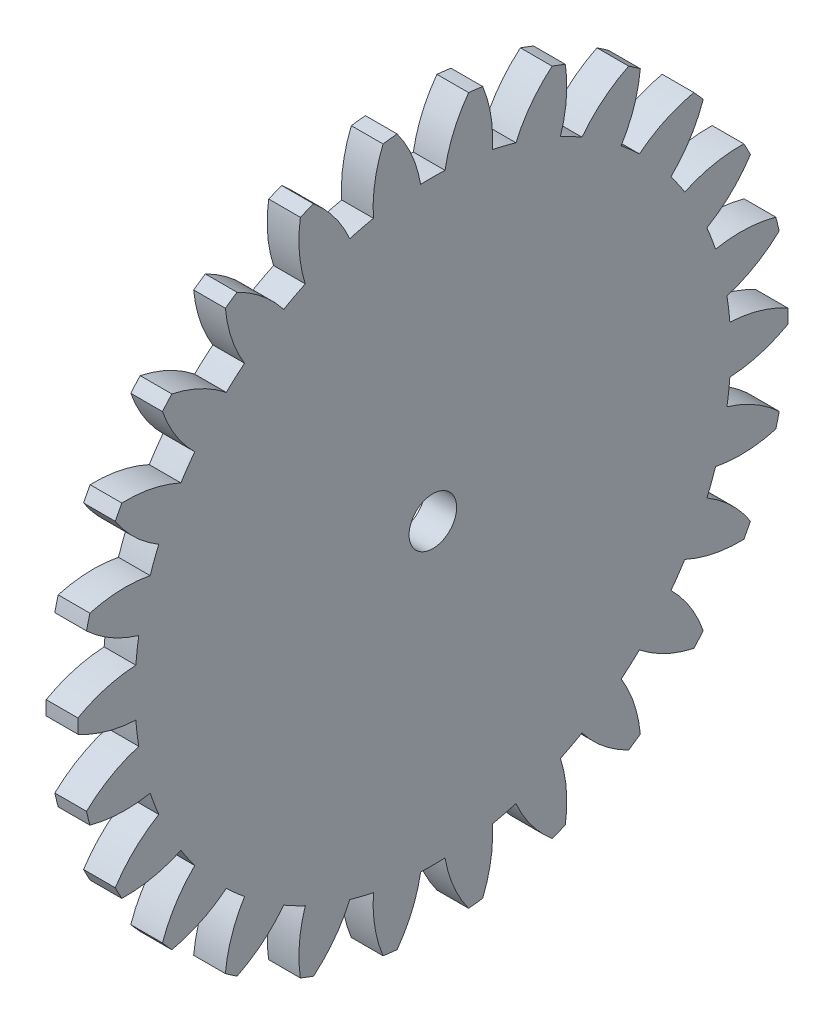
SolidWorks part; units mm, degrees
ref_plane "Plane1" through (0, 0, 0) normal (0, 0, 1) x (1, 0, 0)
ref_plane "Plane2" through (0, 0, 0) normal (0, 1, 0) x (1, 0, 0)
ref_plane "Plane3" through (0, 0, 0) normal (1, 0, 0) x (0, 0, -1)
sketch "HoldingSke" plane through (0, 0, 0) normal (0, 1, 0) x (1, 0, 0)
  line L0 (0, 0) -> (228.2937, -111.3463)
  line L1 (-15, 0) -> (100, 0) construction
  line L2 (0, 0) -> (-2.1039, 2.3779)
  line L3 (0, 0) -> (-11.863, 4.5341)
  line L4 (0, 0) -> (7.762, 3.7858)
  line L5 (0, 0) -> (-47.5972, -17.7524)
  line L6 (0, 0) -> (-2.632, -1.7758)
  line L7 (-2.1039, 2.3779) -> (8.8308, 51.9871)
  line L8 (-76.2, 54.61) -> (-71.1708, 54.61)
  line L9 (-71.009, 38.7566) -> (-53.1078, 45.2721)
  line L10 (-76.2, 71.12) -> (104.1128, 71.12)
  line L11 (0, 0) -> (-3.175, 0)
  line L12 (-76.2, 101.6) -> (-76.0984, 101.6)
  line L13 (24.9733, 27.94) -> (52.9518, 28.4284)
  line L14 (24.9733, 27.94) -> (24.9746, 27.94)
  line L15 (24.9733, 27.94) -> (100.4006, 29.5858)
  circle A0 centre (0, 0) radius 2.3812
  circle A1 centre (0, 0) radius 29.8437
  circle A2 centre (0, 0) radius 38.1
  circle A3 centre (0, 0) radius 2.3812
  dimension "MHD" = 59.6875
  dimension "Hub_dia" = 76.2
  dimension "Bore" = 4.7625
  dimension "MBD" = 4.7625
  dimension "Num_teeth" = 26
  dimension "Pitch" = 254
  dimension "Overall_len" = 50.8
  dimension "Show_teeth" = 26
  dimension "Thickness" = 3.175
  dimension "OAL" = 50.8001
  dimension "T_dim" = 5.0292
  dimension "Ap" = 20
  dimension "H" = 19.05
  dimension "Pitch_radius" = 180.3128
  dimension "Width" = 3.175
  dimension "Backlash" = 0.1016
  dimension "Addendum_fac" = 1
  dimension "Dedendum_fac" = 1.25
  dimension "Clearance_fac" = 0.25
  dimension "Dedendum_add" = 0.0013
sketch "BasProSke" plane through (0, 0, 0) normal (0, 1, 0) x (1, 0, 0)
  line L0 (-10, 0) -> (60, 0) construction
  line L1 (0, 0) -> (0, 35.56)
  line L2 (0, 0) -> (3.175, 0)
  line L3 (3.175, 0) -> (3.175, 35.56)
  line L4 (3.175, 35.56) -> (0, 35.56)
  dimension "Thickness" = 3.175
  dimension "Diameter" = 71.12
revolve "Base-Revolve" add sketch "BasProSke" angle 360 about L0
sketch "TooCutSke" plane through (0, 0, 0) normal (1, 0, 0) x (0, 0, -1)
  line L1 (0, 0) -> (0, 107) construction
  line L2 (0, 0) -> (-2.1714, 32.9485) construction
  line L3 (0, 0) -> (-7.9482, 65.4593) construction
  line L4 (-2.1714, 32.9485) -> (-3.9741, 32.7296) construction
  arc A0 (1.2197, 29.8188) -> (-1.2197, 29.8188) centre (0, 0) ccw
  arc A1 (3.5998, 35.4029) -> (-3.5998, 35.4029) centre (0, 0) ccw
  circle A2 centre (0, 0) radius 33.02 construction
  circle A3 centre (0, 0) radius 31.0287 construction
  arc A4 (-1.2197, 29.8188) -> (-3.5998, 35.4029) centre (-14.235, 27.5707) ccw
  arc A5 (3.5998, 35.4029) -> (1.2197, 29.8188) centre (14.235, 27.5707) ccw
  dimension "Root_dia" = 59.6875
  dimension "Overcut_dia" = 71.1708
  dimension "Pitch_dia" = 66.04
  dimension "Base_dia" = 62.0573
  dimension "Flank_rad" = 13.208
  dimension "Half_ang" = 6.923
  dimension "Half_CT" = 1.8159
extrude "ToothCut" cut sketch "TooCutSke" along normal through all
fillet "Breaks" [suppressed] radius 0.0508
fillet "RootFillets" [suppressed] radius 0.6363
pattern_circular "TeethCuts" count 26 every 13.846 about axis through (-10, 0, 0) along (1, 0, 0) of "ToothCut", "RootFillets", "Breaks"
sketch "HubNeaOneSke" plane through (0, 0, 0) normal (-1, 0, 0) x (0, 0, 1)
  circle A0 centre (0, 0) radius 29.8437
  dimension "Diameter" = 59.6875
extrude "HubNearOne" [suppressed] add sketch "HubNeaOneSke" along normal blind 47.6251
sketch "HubNeaBotSke" plane through (0, 0, 0) normal (-1, 0, 0) x (0, 0, 1)
  circle A0 centre (0, 0) radius 29.8437
  dimension "Diameter" = 59.6875
extrude "HubNearBoth" [suppressed] add sketch "HubNeaBotSke" along normal blind 23.8125
ref_plane "FarPln" through (3.175, 0, 0) normal (1, 0, 0) x (0, 0, -1)
sketch "HubFarSke" plane through (3.175, 0, 0) normal (1, 0, 0) x (0, 0, -1)
  circle A0 centre (0, 0) radius 29.8437
  dimension "Diameter" = 59.6875
extrude "HubFar" [suppressed] add sketch "HubFarSke" along normal blind 23.8125
sketch "BorSke" plane through (0, 0, 0) normal (1, 0, 0) x (0, 0, -1)
  circle A0 centre (0, 0) radius 2.3812
  dimension "Diameter" = 4.7625
extrude "Bore" cut sketch "BorSke" along normal mid plane 101.6001
sketch "KeySke" plane through (0, 0, 0) normal (1, 0, 0) x (0, 0, -1)
  line L0 (-0.127, 0) -> (-0.127, 2.6479)
  line L1 (-0.127, 2.6479) -> (0.127, 2.6479)
  line L2 (0.127, 2.6479) -> (0.127, 0)
  line L3 (0, 0) -> (0, 34) construction
  line L4 (-0.127, 0) -> (0.127, 0)
  dimension "Offset" = 2.648
  dimension "Width" = 0.254
extrude "Keyway" [suppressed] cut sketch "KeySke" along normal mid plane 101.6001
pattern_circular "Keyway2" [suppressed] count 2 every 90 about axis through (-10, 0, 0) along (1, 0, 0)
equation "' \"Pitch@HoldingSke\" = 4"
equation "' \"Num_teeth@HoldingSke\" = 12"
equation "' \"Ap@HoldingSke\" =  20"
equation "' \"Ap@HoldingSke\" = 20"
equation "' \"Width@HoldingSke\" = 0.5"
equation "' \"Hub_dia@HoldingSke\"= 1"
equation "' \"Hub_dia@HoldingSke\" = 1"
equation "' \"Overall_len@HoldingSke\" = 1.0"
equation "' \"Bore@HoldingSke\" = 0.75"
equation "' \"T_dim@HoldingSke\" = 0.85"
equation "' \"Width@KeySke\" = 0.25"
equation "' \"Show_teeth@HoldingSke\" = 13"
equation "' \"Backlash@HoldingSke\" = 0.009"
equation "' \"Addendum_fac@HoldingSke\" = 1.0"
equation "' \"Dedendum_fac@HoldingSke\" = 1.25"
equation "' \"Dedendum_add@HoldingSke\" = 0.00005"
equation "' \"Clearance_fac@HoldingSke\" = 0.25"
equation "' \"Pitch@HoldingSke\" = 0.5"
equation "' \"Num_teeth@HoldingSke\" = 23"
equation "' \"Show_teeth@HoldingSke\" = 23"
equation "' \"Backlash@HoldingSke\" = 0.0375"
equation "\"Overcut_dia@TooCutSke\" = (\"Num_teeth@HoldingSke\" + 2 * \"Addendum_fac@HoldingSke\") / \"Pitch@HoldingSke\" + 0.002"
equation "\"Pitch_dia@TooCutSke\" = \"Num_teeth@HoldingSke\" / \"Pitch@HoldingSke\""
equation "\"Base_dia@TooCutSke\" = \"Num_teeth@HoldingSke\" / \"Pitch@HoldingSke\" * cos((\"Ap@HoldingSke\"  * 3.14159265 / 180))"
equation "\"Root_dia@TooCutSke\" = (\"Num_teeth@HoldingSke\" + 2) / \"Pitch@HoldingSke\" - 2 * (\"Addendum_fac@HoldingSke\" + \"Dedendum_fac@HoldingSke\") / \"Pitch@HoldingSke\" - \"Dedendum_add@HoldingSke\" * 2"
equation "\"Half_ang@TooCutSke\" = 180 / \"Num_teeth@HoldingSke\""
equation "\"Half_CT@TooCutSke\" = \"Num_teeth@HoldingSke\" / \"Pitch@HoldingSke\" * sin((3.14159265 / 2 / \"Num_teeth@HoldingSke\")) / 2 - 7 * \"Backlash@HoldingSke\" / 4"
equation "\"Flank_rad@TooCutSke\" = \"Num_teeth@HoldingSke\" / \"Pitch@HoldingSke\" / 5"
equation "\"Radius@RootFillets\" = \"Clearance_fac@HoldingSke\" / \"Pitch@HoldingSke\" + \"Dedendum_add@HoldingSke\""
equation "\"Break_rad@Breaks\" = 0.02 / \"Pitch@HoldingSke\""
equation "\"Thickness@HoldingSke\" = \"Width@HoldingSke\""
equation "\"OAL@HoldingSke\" = \"Thickness@HoldingSke\""
equation "\"MHD@HoldingSke\" = (\"Num_teeth@HoldingSke\" + 2) / \"Pitch@HoldingSke\" - 2 * (\"Addendum_fac@HoldingSke\" + \"Dedendum_fac@HoldingSke\")  / \"Pitch@HoldingSke\" - \"Dedendum_add@HoldingSke\" * 2"
equation "\"MBD@HoldingSke\" = (\"Num_teeth@HoldingSke\" + 2) / \"Pitch@HoldingSke\" - 2 * (\"Addendum_fac@HoldingSke\" + \"Dedendum_fac@HoldingSke\")  / \"Pitch@HoldingSke\" - \"Dedendum_add@HoldingSke\" * 2 - 0.002"
equation "\"MHD@HoldingSke\" = ((sgn( \"MHD@HoldingSke\" - \"Hub_dia@HoldingSke\" )-1)*( \"MHD@HoldingSke\" - \"Hub_dia@HoldingSke\" ))/-2+ \"Hub_dia@HoldingSke\""
equation "\"MBD@HoldingSke\" = ((sgn( \"MBD@HoldingSke\" - \"Bore@HoldingSke\" )-1)*( \"MBD@HoldingSke\" - \"Bore@HoldingSke\" ))/-2+ \"Bore@HoldingSke\""
equation "\"OAL@HoldingSke\" = ((sgn( \"OAL@HoldingSke\" - \"Overall_len@HoldingSke\" )+1)*( \"OAL@HoldingSke\" - \"Overall_len@HoldingSke\" ))/2 + \"Overall_len@HoldingSke\" + 0.000002"
equation "\"Num_teeth@TeethCuts\" = int( \"Show_teeth@HoldingSke\" ) + 1"
equation "\"Num_teeth@TeethCuts\" = ((sgn( \"Num_teeth@TeethCuts\" - \"Num_teeth@HoldingSke\" )-1)*( \"Num_teeth@TeethCuts\" - \"Num_teeth@HoldingSke\" ))/-2+ \"Num_teeth@HoldingSke\""
equation "\"Num_teeth@TeethCuts\" = ((sgn( \"Num_teeth@TeethCuts\" - 2.0)+1)*( \"Num_teeth@TeethCuts\" - 2.0))/2 +2.0"
equation "\"Angle@TeethCuts\" = 360.0 / \"Num_teeth@HoldingSke\""
equation "\"Diameter@BasProSke\" = (\"Num_teeth@HoldingSke\" + 2 * \"Addendum_fac@HoldingSke\") / \"Pitch@HoldingSke\""
equation "\"Thickness@BasProSke\"  = \"Thickness@HoldingSke\""
equation "' \"Fillet_rad@BasProSke\" =  \"Thickness@HoldingSke\" * 0.05"
equation "' \"Fillet_rad@BasProSke\" = \"Thickness@HoldingSke\" * 0.05"
equation "\"MHD@HoldingSke\" = ((sgn( \"MHD@HoldingSke\" - \"Root_dia@TooCutSke\" )-1)*( \"MHD@HoldingSke\" - \"Root_dia@TooCutSke\" ))/-2+ \"Root_dia@TooCutSke\""
equation "\"Diameter@HubNeaOneSke\" = \"MHD@HoldingSke\""
equation "\"Length@HubNearOne\" = \"OAL@HoldingSke\" - \"Thickness@BasProSke\""
equation "\"Diameter@HubNeaBotSke\" = \"MHD@HoldingSke\""
equation "\"Length@HubNearBoth\" = ( \"OAL@HoldingSke\" - \"Thickness@BasProSke\" ) / 2.0"
equation "\"Thickness@FarPln\" = \"Thickness@BasProSke\""
equation "\"Diameter@HubFarSke\" = \"MHD@HoldingSke\""
equation "\"Length@HubFar\" = ( \"OAL@HoldingSke\" - \"Thickness@BasProSke\" ) / 2.0"
equation "\"Diameter@BorSke\" = \"MBD@HoldingSke\""
equation "\"D1@Bore\" = \"OAL@HoldingSke\" * 2.0"
equation "\"D1@Keyway\" = \"OAL@HoldingSke\" * 2.0"
equation "\"Offset@KeySke\" = \"T_dim@HoldingSke\" - \"MBD@HoldingSke\" / 2.0"
